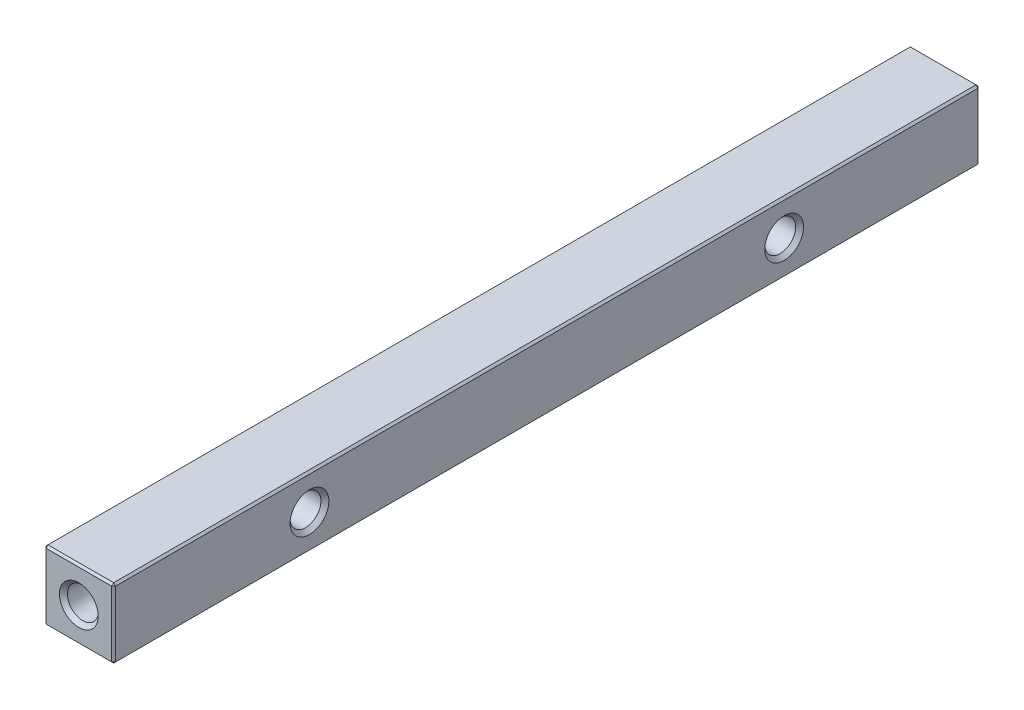
SolidWorks part; units mm, degrees
ref_plane "Front Plane" through (0, 0, 0) normal (0, 0, 1) x (1, 0, 0)
ref_plane "Top Plane" through (0, 0, 0) normal (0, 1, 0) x (1, 0, 0)
ref_plane "Right Plane" through (0, 0, 0) normal (1, 0, 0) x (0, 0, -1)
sketch "Sketch1" plane through (0, 0, 0) normal (0, 0, 1) x (1, 0, 0)
  line L1 (-4.4, 4.4) -> (4.4, 4.4)
  line L2 (-4.4, 4.4) -> (-4.4, -4.4)
  line L3 (-4.4, -4.4) -> (4.4, -4.4)
  line L4 (4.4, 4.4) -> (4.4, -4.4)
  line L5 (-4.4, 4.4) -> (4.4, -4.4) construction
  line L6 (-4.4, -4.4) -> (4.4, 4.4) construction
  point P0 (0, 0)
  dimension "D1" = 8.8
extrude "Boss-Extrude1" add sketch "Sketch1" along normal mid plane 109.5
sketch "Sketch2" plane through (0, 0, 54.75) normal (0, 0, 1) x (1, 0, 0)
  circle A0 centre (0, 0) radius 1.95
  dimension "D1" = 3.9
extrude "Cut-Extrude1" cut sketch "Sketch2" against normal blind 8
mirror "Mirror1" about plane through (0, 0, 0) normal (0, 0, 1) of "Cut-Extrude1"
sketch "Sketch3" plane through (4.4, 0, 0) normal (1, 0, 0) x (0, 0, -1)
  line L0 (-54.75, 0) -> (54.75, 0) construction
  line L1 (-54.75, -4.4) -> (-54.75, 4.4) construction
  line L2 (54.75, -4.4) -> (54.75, 4.4) construction
  line L3 (0, 4.4) -> (0, -4.4) construction
  line L4 (-54.75, 4.4) -> (54.75, 4.4) construction
  line L5 (-54.75, -4.4) -> (54.75, -4.4) construction
  circle A0 centre (-30, 0) radius 1.95
  circle A1 centre (30, 0) radius 1.95
  dimension "D1" = 3.9
  dimension "D2" = 60
extrude "Cut-Extrude2" cut sketch "Sketch3" against normal up to next
chamfer "Chamfer1" distance 0.5 angle 45 6 edges at (-4.4, 0, -31.95) (4.4, 0, -28.05) (4.4, 0, 28.05) (-4.4, 0, 28.05) (1.95, 0, -54.75) (1.95, 0, 54.75)
chamfer "Chamfer2" distance 0.25 angle 45 12 edges at (-4.4, -4.4, 0) (0, -4.4, 54.75) (4.4, -4.4, 0) (0, -4.4, -54.75) (4.4, 4.4, 0) (4.4, 0, -54.75) (0, 4.4, -54.75) (-4.4, 0, -54.75) (-4.4, 4.4, 0) (-4.4, 0, 54.75) (0, 4.4, 54.75) (4.4, 0, 54.75)
